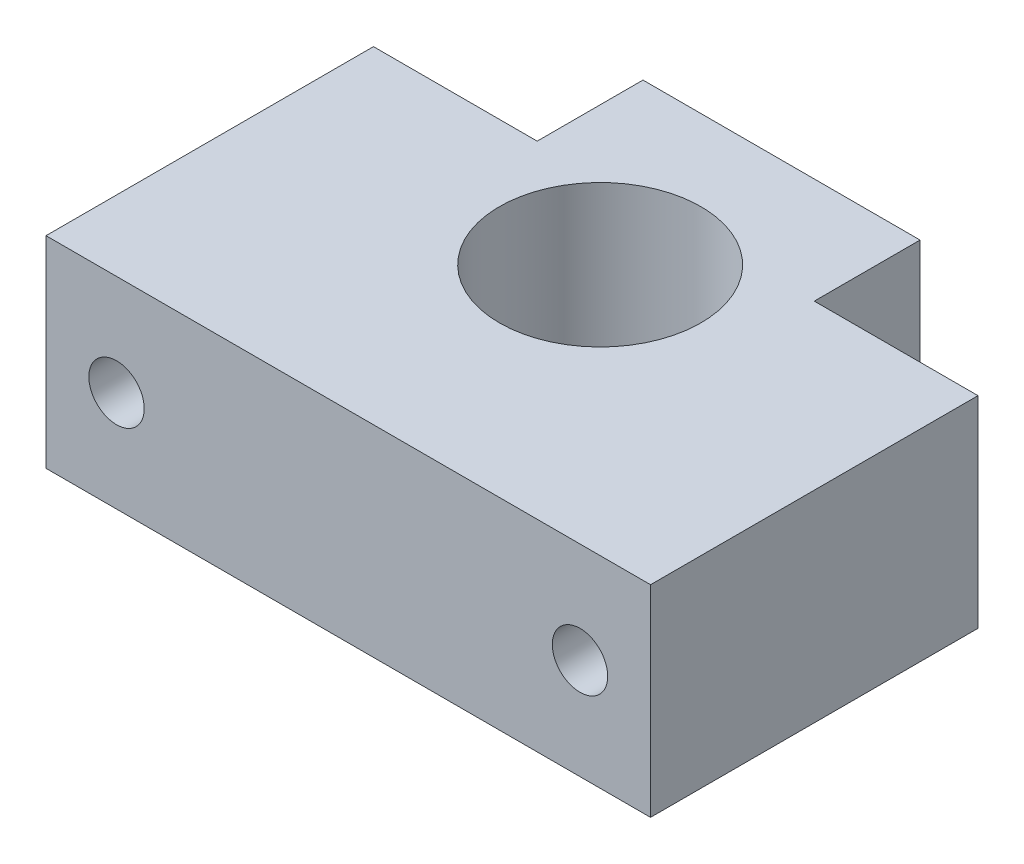
SolidWorks part; units mm, degrees
material "Chrome Stainless Steel"
ref_plane "Front Plane" through (0, 0, 0) normal (0, 0, 1) x (1, 0, 0)
ref_plane "Top Plane" through (0, 0, 0) normal (0, 1, 0) x (1, 0, 0)
ref_plane "Right Plane" through (0, 0, 0) normal (1, 0, 0) x (0, 0, -1)
sketch "Sketch1" plane through (0, 0, 0) normal (0, 1, 0) x (1, 0, 0)
  line L0 (30, 43) -> (30, -0.4221) construction
  line L5 (0, 32.5) -> (0, 0)
  line L8 (60, 32.5) -> (43.75, 32.5)
  line L9 (43.75, 43) -> (43.75, 32.5)
  line L12 (0, 32.5) -> (16.25, 32.5)
  line L13 (16.25, 43) -> (16.25, 32.5)
  line L14 (60, 0) -> (60, 32.5)
  line L15 (60, 0) -> (0, 0)
  line L16 (16.25, 43) -> (43.75, 43)
  point P11 (43.75, 37.75)
  dimension "D4" = 27.5
extrude "Boss-Extrude1" add sketch "Sketch1" along normal blind 20
sketch "Sketch2" plane through (0, 20, 0) normal (0, 1, 0) x (1, 0, 0)
  line L0 (30, 43) -> (30, 0) construction
  line L1 (43.75, 43) -> (16.25, 43) construction
  line L2 (0, 0) -> (60, 0) construction
  line L3 (0, 25) -> (60, 25) construction
  line L4 (0, 32.5) -> (0, 0) construction
  line L5 (60, 0) -> (60, 32.5) construction
  circle A0 centre (30, 25) radius 10
  dimension "D1" = 25
extrude "Cut-Extrude1" cut sketch "Sketch2" against normal through all
sketch "Sketch4" plane through (0, 20, 0) normal (0, 1, 0) x (1, 0, 0)
  line L0 (30, 43) -> (30, 0) construction
  line L1 (43.75, 43) -> (16.25, 43) construction
  line L2 (0, 0) -> (60, 0) construction
  line L3 (20, 25) -> (60, 25) construction
  line L4 (60, 0) -> (60, 32.5) construction
  circle A0 centre (30, 25) radius 10 construction
  circle A1 centre (30, 25) radius 9
  circle A2 centre (30, 25) radius 5
sketch "Sketch6" plane through (0, 0, 0) normal (0, 0, 1) x (1, 0, 0)
  line L0 (60, 20) -> (60, 0) construction
  line L2 (0, 0) -> (60, 0) construction
  circle A0 centre (7, 10) radius 2.75
  circle A1 centre (53, 10) radius 2.75
  dimension "D1" = 5.5
  dimension "D2" = 5.5
  dimension "D3" = 46
  dimension "D4" = 7
  dimension "D5" = 10
  dimension "D6" = 10
extrude "Cut-Extrude2" cut sketch "Sketch6" against normal blind 10
